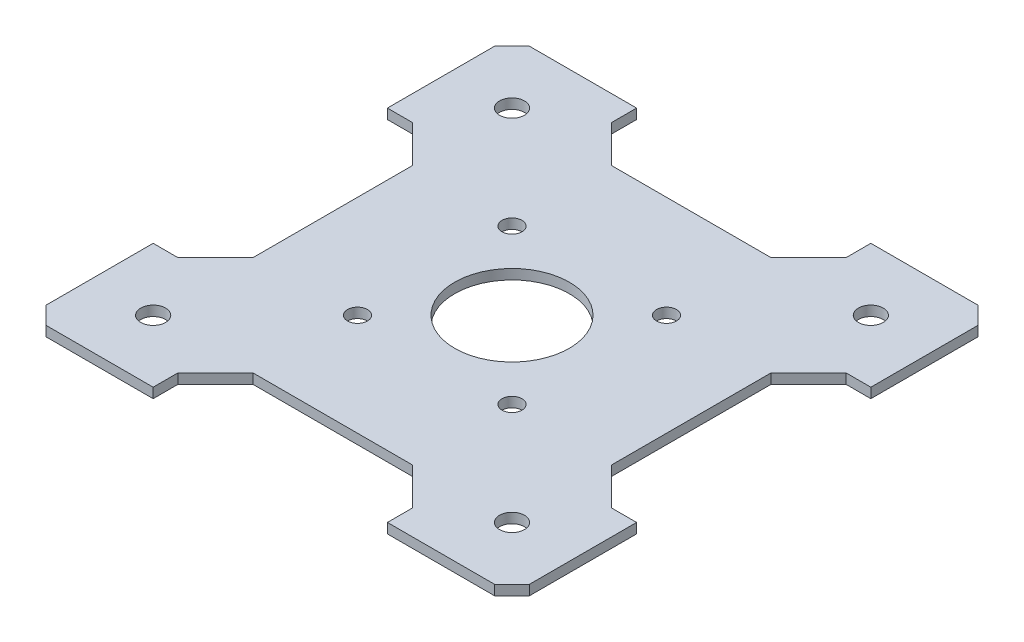
SolidWorks part; units mm, degrees
material "1060 Alloy"
ref_plane "Front Plane" through (0, 0, 0) normal (0, 0, 1) x (1, 0, 0)
ref_plane "Top Plane" through (0, 0, 0) normal (0, 1, 0) x (1, 0, 0)
ref_plane "Right Plane" through (0, 0, 0) normal (1, 0, 0) x (0, 0, -1)
sketch "Sketch1" plane through (0, 0, 0) normal (0, 1, 0) x (1, 0, 0)
  line L1 (-36, 36) -> (36, 36)
  line L2 (-36, 36) -> (-36, -36)
  line L3 (-36, -36) -> (36, -36)
  line L4 (36, 36) -> (36, -36)
  line L5 (-36, 36) -> (36, -36) construction
  line L6 (-36, -36) -> (36, 36) construction
  point P0 (0, 0)
  dimension "D1" = 72
  dimension "D2" = 72
extrude "Boss-Extrude1" add sketch "Sketch1" along normal blind 2
sketch "Sketch5" plane through (0, 2, 0) normal (0, 1, 0) x (1, 0, 0)
  line L0 (0, 36) -> (0, -36) construction
  line L1 (-48.5, -23.5) -> (-23.5, -23.5)
  line L2 (-48.5, -23.5) -> (-48.5, -48.5)
  line L3 (-48.5, -48.5) -> (-23.5, -48.5)
  line L4 (-23.5, -23.5) -> (-23.5, -48.5)
  line L5 (-48.5, -23.5) -> (-23.5, -48.5) construction
  line L6 (-48.5, -48.5) -> (-23.5, -23.5) construction
  line L7 (36, 36) -> (-36, 36) construction
  line L8 (-36, -36) -> (36, -36) construction
  line L9 (-36, 0) -> (36, 0) construction
  line L10 (-36, 36) -> (-36, -36) construction
  line L11 (36, -36) -> (36, 36) construction
  line L12 (23.5, -23.5) -> (23.5, -48.5)
  line L13 (48.5, -48.5) -> (23.5, -48.5)
  line L14 (48.5, -23.5) -> (48.5, -48.5)
  line L15 (48.5, -23.5) -> (23.5, -23.5)
  line L16 (48.5, 23.5) -> (48.5, 48.5)
  line L17 (48.5, 23.5) -> (23.5, 23.5)
  line L18 (23.5, 23.5) -> (23.5, 48.5)
  line L19 (48.5, 48.5) -> (23.5, 48.5)
  line L20 (-23.5, 23.5) -> (-23.5, 48.5)
  line L21 (-48.5, 48.5) -> (-23.5, 48.5)
  line L22 (-48.5, 23.5) -> (-48.5, 48.5)
  line L23 (-48.5, 23.5) -> (-23.5, 23.5)
  point P0 (-36, -36)
  dimension "D1" = 25
extrude "Boss-Extrude2" add sketch "Sketch5" against normal up to surface (2 mm away) up to face at (0, 0, 0)
sketch "Sketch3" plane through (0, 2, 0) normal (0, 1, 0) x (1, 0, 0)
  line L0 (-48.5, -36) -> (-23.5, -36) construction
  line L1 (-48.5, -23.5) -> (-48.5, -48.5) construction
  line L2 (-36, -23.5) -> (-36, -48.5) construction
  line L3 (-36, -23.5) -> (-48.5, -23.5) construction
  line L4 (-48.5, -48.5) -> (-23.5, -48.5) construction
  line L5 (0, 36) -> (0, -36) construction
  line L6 (23.5, 36) -> (-23.5, 36) construction
  line L7 (-36, 0) -> (36, 0) construction
  line L8 (-36, 23.5) -> (-36, -23.5) construction
  line L9 (36, -23.5) -> (36, 23.5) construction
  line L10 (-23.5, -36) -> (23.5, -36) construction
  circle A0 centre (-15.5, 15.5) radius 2
  circle A1 centre (15.5, 15.5) radius 2
  circle A2 centre (15.5, -15.5) radius 2
  circle A3 centre (-15.5, -15.5) radius 2
  circle A4 centre (0, 0) radius 11.5
  circle A5 centre (-36, -36) radius 2.5
  circle A6 centre (36, -36) radius 2.5
  circle A7 centre (36, 36) radius 2.5
  circle A8 centre (-36, 36) radius 2.5
  dimension "D1" = 4
  dimension "D8" = 23
  dimension "D9" = 5
  dimension "D2" = 15.5
  dimension "D3" = 15.5
  dimension "D6" = 31
  dimension "D7" = 31
  dimension "D4" = 2
  dimension "D5" = 2
extrude "Cut-Extrude1" cut sketch "Sketch3" against normal through all
chamfer "Chamfer1" distance 7.5 angle 45 8 edges at (-36, 1, 23.5) (-36, 1, -23.5) (-23.5, 1, -36) (23.5, 1, -36) (36, 1, -23.5) (36, 1, 23.5) (23.5, 1, 36) (-23.5, 1, 36)
chamfer "Chamfer2" distance 3.5 angle 45 4 edges at (-48.5, 1, -48.5) (48.5, 1, -48.5) (48.5, 1, 48.5) (-48.5, 1, 48.5)
equation "\"Stepper Motor Width\"= 42mm"
equation "\"Stepper Motor Length\"= 42mm"
equation "\"Extra Spacing\"= 15mm"
equation "\"Plate Thickness\"= 2mm"
equation "\"Screw X-Offset\"= 15.5mm"
equation "\"Screw Y-Offset\"= 15.5mm"
equation "\"D1@Sketch1\"=\"Stepper Motor Width\"+\"Extra Spacing\"*2"
equation "\"D2@Sketch1\"=\"Stepper Motor Length\"+\"Extra Spacing\"*2"
equation "\"D1@Boss-Extrude1\"=\"Plate Thickness\""
equation "\"Stepper Screw Diameter\"= 4mm"
equation "\"D6@Sketch3\"=\"Screw X-Offset\"*2"
equation "\"Shaft Diameter\"= 23mm"
equation "\"D8@Sketch3\"=\"Shaft Diameter\""
equation "\"Plate Mount Screw Diameter\"= 5mm"
equation "\"D9@Sketch3\"=\"Plate Mount Screw Diameter\""
